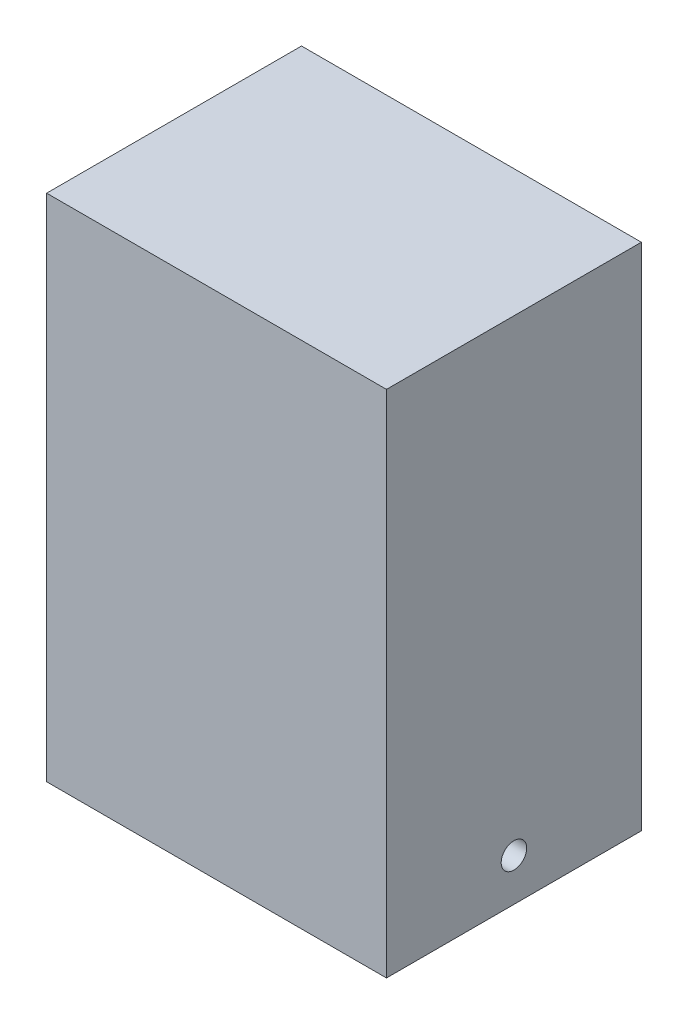
SolidWorks part; units mm, degrees
ref_plane "Front Plane" through (0, 0, 0) normal (0, 0, 1) x (1, 0, 0)
ref_plane "Top Plane" through (0, 0, 0) normal (0, 1, 0) x (1, 0, 0)
ref_plane "Right Plane" through (0, 0, 0) normal (1, 0, 0) x (0, 0, -1)
sketch "Sketch1" plane through (0, 0, 0) normal (0, 0, 1) x (1, 0, 0)
  line L1 (-20, -30) -> (20, -30)
  line L2 (-20, -30) -> (-20, 30)
  line L3 (-20, 30) -> (20, 30)
  line L4 (20, -30) -> (20, 30)
  line L5 (-20, -30) -> (20, 30) construction
  line L6 (-20, 30) -> (20, -30) construction
  point P0 (0, 0)
  dimension "D1" = 40
  dimension "D2" = 60
extrude "Boss-Extrude1" add sketch "Sketch1" along normal blind 30
sketch "Sketch2" plane through (20, 0, 0) normal (1, 0, 0) x (0, 0, -1)
  line L0 (-15, 30) -> (-15, -30) construction
  line L1 (-30, 30) -> (0, 30) construction
  line L2 (-30, -30) -> (0, -30) construction
  circle A0 centre (-15, -25) radius 1.5
  dimension "D1" = 3
  dimension "D2" = 5
extrude "Cut-Extrude1" cut sketch "Sketch2" against normal through all
